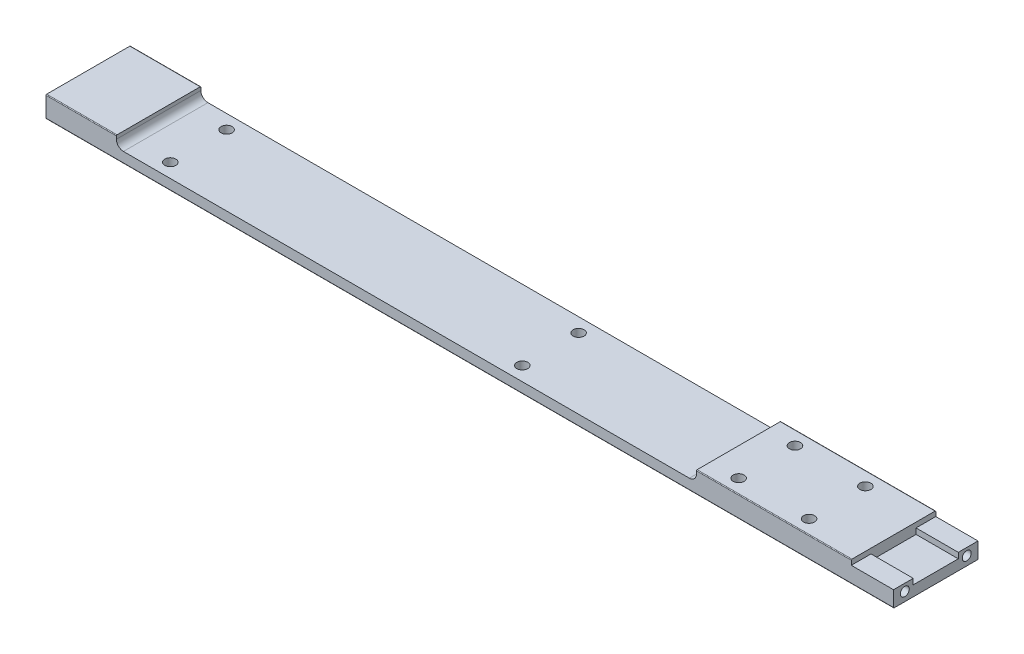
SolidWorks part; units mm, degrees
material "6061 Alloy"
ref_plane "Front Plane" through (0, 0, 0) normal (0, 0, 1) x (1, 0, 0)
ref_plane "Top Plane" through (0, 0, 0) normal (0, 1, 0) x (1, 0, 0)
ref_plane "Right Plane" through (0, 0, 0) normal (1, 0, 0) x (0, 0, -1)
sketch "Sketch1" plane through (0, 0, 0) normal (0, 1, 0) x (1, 0, 0)
  line L1 (191.135, -19.05) -> (-191.135, -19.05)
  line L2 (191.135, -19.05) -> (191.135, 19.05)
  line L3 (191.135, 19.05) -> (-191.135, 19.05)
  line L4 (-191.135, -19.05) -> (-191.135, 19.05)
  line L5 (191.135, -19.05) -> (-191.135, 19.05) construction
  line L6 (191.135, 19.05) -> (-191.135, -19.05) construction
  point P0 (0, 0)
  dimension "Length" = 382.27
  dimension "Width" = 38.1
sketch "Sketch2" plane through (0, 0, 0) normal (1, 0, 0) x (0, 0, -1)
  line L0 (19.05, 4.7625) -> (19.05, -4.7625) construction
  point P2 (19.05, 0)
  dimension "Thickness" = 9.525
sketch "Sketch3" plane through (0, 0, 0) normal (0, 1, 0) x (1, 0, 0)
  line L1 (-191.135, 19.05) -> (191.135, 19.05)
  line L2 (-191.135, 19.05) -> (-191.135, -19.05)
  line L3 (-191.135, -19.05) -> (191.135, -19.05)
  line L4 (191.135, 19.05) -> (191.135, -19.05)
extrude "Boss-Extrude1" add sketch "Sketch3" against normal up to vertex (4.7625 mm away) and the other way up to vertex (4.7625 mm away) up to point (0, -4.7625, -19.05) other way up to point (0, 4.7625, -19.05)
fillet "Fillet1" radius 0.3143 4 edges at (0, -4.7625, 19.05) (0, -4.7625, -19.05) (0, 4.7625, -19.05) (0, 4.7625, 19.05)
sketch "Sketch4" plane through (-191.135, 0, 0) normal (-1, 0, 0) x (0, 0, 1)
  line L0 (0, -0.762) -> (13.97, -0.762) construction
  line L1 (0, -0.762) -> (-13.97, -0.762) construction
  line L2 (0, -0.762) -> (0, 0) construction
  dimension "D1" = 13.97
  dimension "D2" = 13.97
  dimension "D3" = 0.762
hole_wizard "Tap Drill for #10-32 Tap1" positions "Sketch5" profile "Sketch6" hole size "#10-32" standard "ANSI Inch"
sketch "Sketch5" plane through (-191.135, 0, 0) normal (-1, 0, 0) x (0, 0, 1)
  point P0 (-13.97, -0.762)
  point P3 (13.97, -0.762)
sketch "Sketch6" plane through (-191.135, -0.762, -13.97) normal (0, 1, 0) x (0, 0, 1)
  line L0 (0, 0) -> (0, 26.6133)
  line L1 (0, 26.6133) -> (2.0193, 25.4)
  line L2 (2.0193, 25.4) -> (2.0193, 0)
  line L5 (2.0193, 0) -> (0, 0)
  line L10 (0, 26.6133) -> (-2.0193, 25.4) construction
  line L11 (0, -6.35) -> (0, 107.95) construction
  dimension "Hole Dia." = 4.0386
  dimension "Hole Depth" = 25.4
  dimension "Drill Angle" = 118
hole_wizard "Tap Drill for #10-32 Tap2" positions "Sketch7" profile "Sketch8" hole size "#10-32" standard "ANSI Inch"
sketch "Sketch7" plane through (191.135, 0, 0) normal (1, 0, 0) x (0, 0, -1)
  point P0 (-13.97, -0.762)
  point P3 (13.97, -0.762)
sketch "Sketch8" plane through (191.135, -0.762, 13.97) normal (0, 1, 0) x (0, 0, -1)
  line L0 (0, 0) -> (0, 26.6133)
  line L1 (0, 26.6133) -> (2.0193, 25.4)
  line L2 (2.0193, 25.4) -> (2.0193, 0)
  line L5 (2.0193, 0) -> (0, 0)
  line L10 (0, 26.6133) -> (-2.0193, 25.4) construction
  line L11 (0, -6.35) -> (0, 107.95) construction
  dimension "Hole Dia." = 4.0386
  dimension "Hole Depth" = 25.4
  dimension "Drill Angle" = 118
sketch "Sketch10" plane through (0, 0, -19.05) normal (0, 0, -1) x (-1, 0, 0)
  line L0 (159.385, 4.7625) -> (159.385, 3.175)
  line L1 (-191.135, 4.7625) -> (191.135, 4.7625) construction
  line L2 (156.21, 0) -> (-99.06, 0)
  line L3 (-102.235, 3.175) -> (-102.235, 4.7625)
  line L4 (-102.235, 4.7625) -> (159.385, 4.7625)
  line L5 (-191.135, -3.175) -> (-191.135, 33.0219) construction
  line L6 (191.135, -3.175) -> (191.135, 33.0219) construction
  line L7 (-191.135, 4.7625) -> (-172.085, 4.7625)
  line L8 (-172.085, 4.7625) -> (-172.085, 2.4765)
  line L9 (-172.085, 2.4765) -> (-191.135, 2.4765)
  line L10 (-191.135, -4.4482) -> (-191.135, 4.4482) construction
  line L11 (-191.135, 2.4765) -> (-191.135, 4.7625)
  arc A0 (159.385, 3.175) -> (156.21, 0) centre (156.21, 3.175) cw
  arc A1 (-99.06, 0) -> (-102.235, 3.175) centre (-99.06, 3.175) cw
  point P12 (159.385, 0)
  dimension "D4" = 3.175
  dimension "D1" = 88.9
  dimension "D2" = 31.75
  dimension "D3" = 4.7625
  dimension "D5" = 19.05
  dimension "D6" = 2.286
extrude "Cut-Extrude1" cut sketch "Sketch10" against normal through all
sketch "Sketch13" plane through (0, -4.7625, 0) normal (0, -1, 0) x (1, 0, 0)
  line L0 (191.135, 0) -> (146.685, 0) construction
  line L1 (191.135, 18.7357) -> (191.135, -18.7357) construction
  line L2 (146.685, 0) -> (146.685, 12.7) construction
  line L3 (146.685, 12.7) -> (114.935, 12.7) construction
  line L4 (114.935, 12.7) -> (114.935, -12.7) construction
  line L5 (114.935, -12.7) -> (146.685, -12.7) construction
  line L6 (146.685, -12.7) -> (146.685, 0) construction
  dimension "D1" = 44.45
  dimension "D2" = 31.75
  dimension "D3" = 31.75
hole_wizard "#10 Clearance Hole1" positions "Sketch14" profile "Sketch15" hole size "#10" standard "ANSI Inch" end condition through all
sketch "Sketch14" plane through (0, -4.7625, 0) normal (0, -1, 0) x (-1, 0, 0)
  point P0 (-114.935, 12.7)
  point P3 (-146.685, 12.7)
  point P6 (-146.685, -12.7)
  point P9 (-114.935, -12.7)
sketch "Sketch15" plane through (114.935, -4.7625, -12.7) normal (1, 0, 0) x (0, 0, -1)
  line L0 (0, 0) -> (0, 9.525)
  line L1 (0, 9.525) -> (2.4892, 9.525)
  line L2 (2.4892, 9.525) -> (2.4892, 3.1411)
  line L3 (2.4892, 3.1411) -> (5.2197, 0)
  line L5 (5.2197, 0) -> (0, 0)
  line L6 (-2.4892, 3.1411) -> (-5.2197, 0) construction
  line L11 (0, -6.35) -> (0, 107.95) construction
  dimension "Thru Hole Dia." = 4.9784
  dimension "Thru Hole Depth" = 9.525
  dimension "Near C'Sink Dia." = 10.4394
  dimension "Near C'Sink Angle" = 82
sketch "Sketch17" plane through (0, 2.4765, 0) normal (0, 1, 0) x (1, 0, 0)
  line L23 (191.135, 0) -> (191.135, 10.16)
  line L24 (191.135, -19.05) -> (191.135, 19.05) construction
  line L25 (191.135, 10.16) -> (172.085, 10.16)
  line L26 (172.085, -19.05) -> (172.085, 19.05) construction
  line L27 (172.085, 10.16) -> (172.085, -10.16)
  line L28 (172.085, -10.16) -> (191.135, -10.16)
  line L29 (191.135, -10.16) -> (191.135, 0)
extrude "Cut-Extrude2" cut sketch "Sketch17" against normal blind 2.54
sketch "Sketch18" plane through (0, 0, 0) normal (0, 1, 0) x (1, 0, 0)
  line L0 (30.0312, 19.05) -> (17.3312, 19.05) construction
  line L1 (99.06, 19.05) -> (-156.21, 19.05) construction
  line L2 (30.0312, 19.584) -> (30.0312, 16.7333) construction
  line L3 (17.3312, 19.05) -> (17.3312, 12.7) construction
  line L4 (17.3312, 12.7) -> (17.3312, -12.7) construction
  line L5 (17.3312, -12.7) -> (17.3312, -19.05) construction
  line L6 (99.06, -19.05) -> (-156.21, -19.05) construction
  line L7 (17.3312, -19.05) -> (-141.4188, -19.05) construction
  line L8 (-141.4188, -19.05) -> (-141.4188, -12.7) construction
  line L9 (-141.4188, -12.7) -> (-141.4188, 12.7) construction
  line L10 (-141.4188, 12.7) -> (-141.4188, 19.05) construction
  dimension "D1" = 6.35
  dimension "D2" = 25.4
  dimension "D3" = 6.35
  dimension "D4" = 25.4
hole_wizard "#10 Clearance Hole2" positions "Sketch19" profile "Sketch20" hole size "#10" standard "ANSI Inch" end condition through all
sketch "Sketch19" plane through (0, 0, 0) normal (0, 1, 0) x (1, 0, 0)
  point P0 (-141.4188, 12.7)
  point P3 (-141.4188, -12.7)
  point P6 (17.3312, 12.7)
  point P9 (17.3312, -12.7)
sketch "Sketch20" plane through (-141.4188, 0, -12.7) normal (1, 0, 0) x (0, 0, 1)
  line L0 (0, 0) -> (0, 4.7625)
  line L1 (0, 4.7625) -> (2.4892, 4.7625)
  line L2 (2.4892, 4.7625) -> (2.4892, 0)
  line L5 (2.4892, 0) -> (0, 0)
  line L11 (0, -6.35) -> (0, 107.95) construction
  dimension "Thru Hole Dia." = 4.9784
  dimension "Thru Hole Depth" = 4.7625
equation "\"D1@Fillet1\" = \"Thickness@Sketch2\" * .033"
